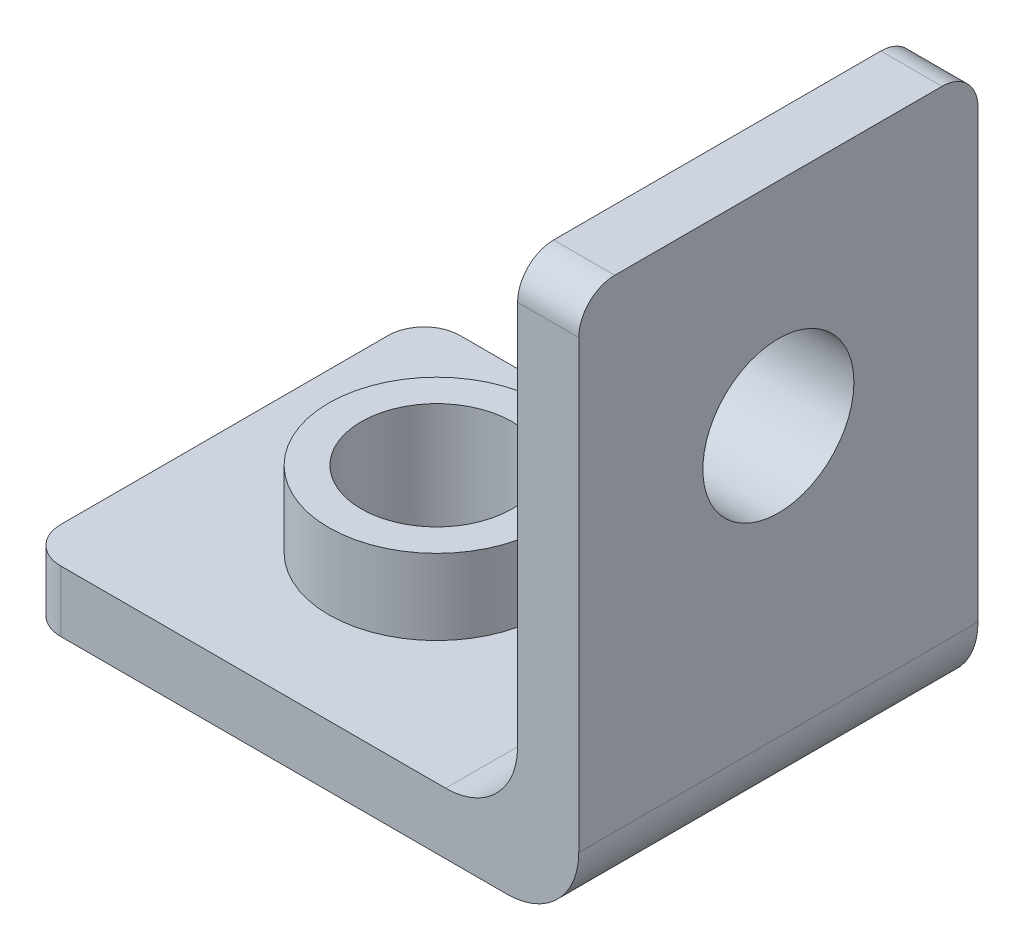
SolidWorks part; units mm, degrees
ref_plane "前视基准面" through (0, 0, 0) normal (0, 0, 1) x (1, 0, 0)
ref_plane "上视基准面" through (0, 0, 0) normal (0, 1, 0) x (1, 0, 0)
ref_plane "右视基准面" through (0, 0, 0) normal (1, 0, 0) x (0, 0, -1)
other "Configuration Table"
sketch "草图1" plane through (0, 0, 0) normal (0, 0, 1) x (1, 0, 0)
  line L0 (0, 0) -> (0, 15.4)
  line L1 (0, 15.4) -> (-1.7, 15.4)
  line L2 (-1.7, 15.4) -> (-1.7, 1.7)
  line L3 (-1.7, 1.7) -> (-15.4, 1.7)
  line L4 (-15.4, 1.7) -> (-15.4, 0)
  line L5 (-15.4, 0) -> (0, 0)
  dimension "D1" = 1.7
  dimension "D2" = 1.7
  dimension "D3" = 15.4
  dimension "D4" = 15.4
  dimension "D5" = 13.7
  dimension "D6" = 90
extrude "凸台-拉伸1" add sketch "草图1" along normal blind 11.1
fillet "圆角1" radius 1 4 edges at (-15.4, 0.85, 11.1) (-15.4, 0.85, 0) (-0.85, 15.4, 0) (-0.85, 15.4, 11.1)
sketch "草图2" plane through (0, 0, 0) normal (1, 0, 0) x (0, 0, -1)
  circle A1 centre (-5.55, 9.5) radius 3
  dimension "D3" = 6
sketch "草图3" plane through (0, 0, 0) normal (0, 1, 0) x (1, 0, 0)
  circle A0 centre (-9.5, -5.55) radius 3
  dimension "D2" = 6
extrude "凸台-拉伸2" add sketch "草图3" along normal blind 3.8
extrude "凸台-拉伸3" add sketch "草图2" against normal blind 3.8 contours A1
fillet "圆角2" radius 2 2 edges at (-1.7, 1.7, 5.55) (0, 0, 5.55)
hole_wizard "M5 螺纹孔3" positions "草图10" profile "草图11" tap size "M5" standard "ISO" end condition through all
sketch "草图10" plane through (0, 0, 0) normal (1, 0, 0) x (0, 0, -1)
  point P0 (-5.55, 9.5)
sketch "草图11" plane through (0, 9.5, 5.55) normal (0, 1, 0) x (0, 0, -1)
  line L0 (0, 0) -> (0, 15.4)
  line L1 (0, 15.4) -> (2.1, 15.4)
  line L2 (2.1, 15.4) -> (2.1, 0)
  line L5 (2.1, 0) -> (0, 0)
  line L11 (0, -6.35) -> (0, 107.95) construction
  dimension "通孔螺纹孔钻头直径" = 4.2
  dimension "通孔螺纹孔钻头深度" = 15.4
cosmetic thread "孔螺蚊线3" parameters "D2"=5
hole_wizard "M5 螺纹孔4" positions "草图12" profile "草图13" tap size "M5" standard "ISO" end condition through all
sketch "草图12" plane through (0, 0, 0) normal (0, -1, 0) x (-1, 0, 0)
  point P0 (9.5, -5.55)
sketch "草图13" plane through (-9.5, 0, 5.55) normal (1, 0, 0) x (0, 0, -1)
  line L0 (0, 0) -> (0, 15.4)
  line L1 (0, 15.4) -> (2.1, 15.4)
  line L2 (2.1, 15.4) -> (2.1, 0)
  line L5 (2.1, 0) -> (0, 0)
  line L11 (0, -6.35) -> (0, 107.95) construction
  dimension "通孔螺纹孔钻头直径" = 4.2
  dimension "通孔螺纹孔钻头深度" = 15.4
cosmetic thread "孔螺蚊线4" parameters "D2"=5
